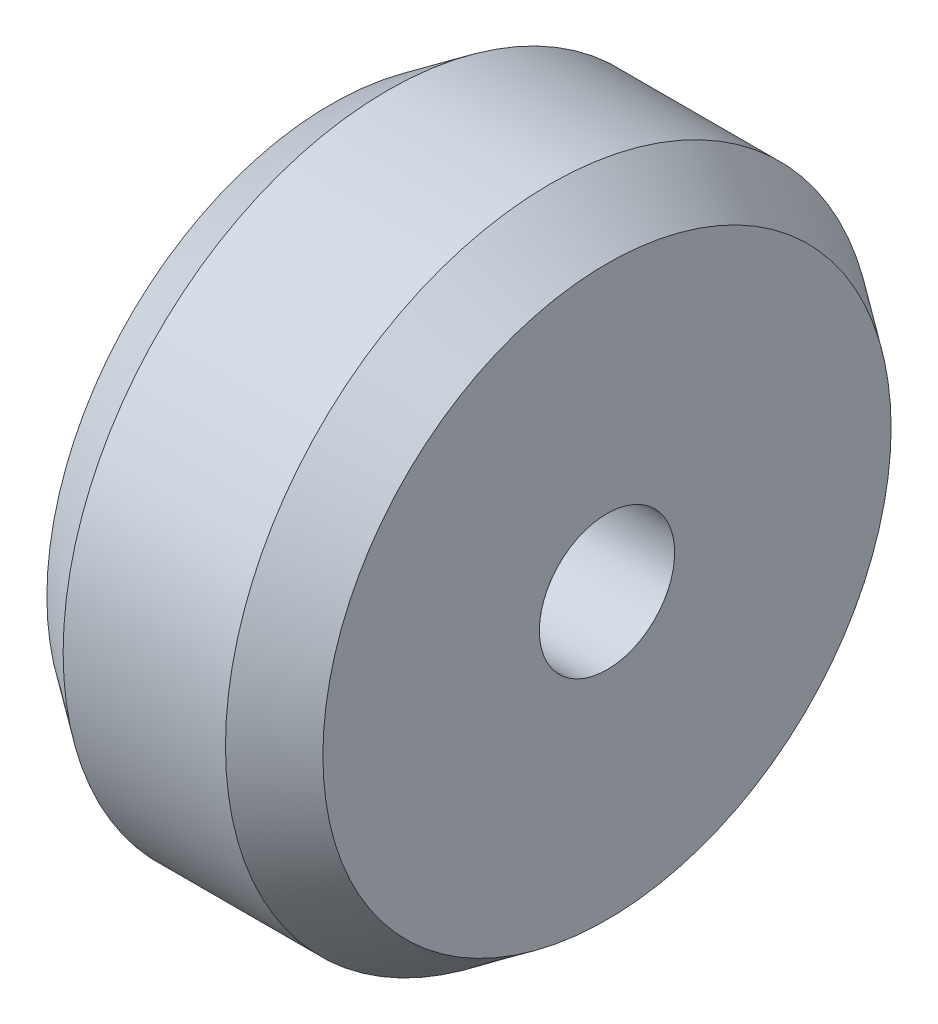
SolidWorks part; units mm, degrees
ref_plane "Front Plane" through (0, 0, 0) normal (0, 0, 1) x (1, 0, 0)
ref_plane "Top Plane" through (0, 0, 0) normal (0, 1, 0) x (1, 0, 0)
ref_plane "Right Plane" through (0, 0, 0) normal (1, 0, 0) x (0, 0, -1)
sketch "Croquis1" plane through (0, 0, 0) normal (0, 0, 1) x (1, 0, 0)
  line L0 (-46.2094, 0) -> (2264.262, 0) construction
  line L1 (0, -46.2094) -> (0, 2264.262) construction
  line L2 (5.1, 2.5) -> (-5.1, 2.5)
  line L3 (-5.1, 2.5) -> (-5.1, 10.5)
  line L4 (-5.1, 10.5) -> (-3, 12)
  line L5 (-3, 12) -> (3, 12)
  line L7 (5.1, 10.5) -> (3, 12)
  line L8 (5.1, 2.5) -> (5.1, 10.5)
  dimension "D1" = 5
  dimension "D2" = 24
  dimension "D3" = 10.2
  dimension "D4" = 6
  dimension "D5" = 21
revolve "Revolución1" add sketch "Croquis1" angle 360 about L0
